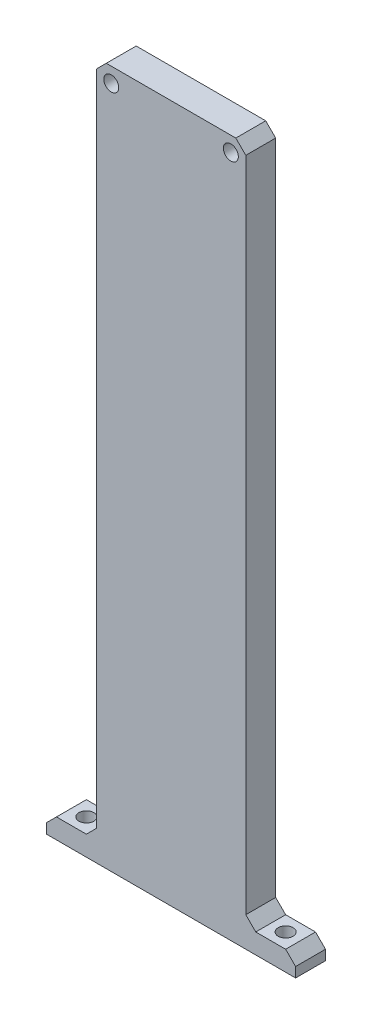
SolidWorks part; units mm, degrees
ref_plane "Front Plane" through (0, 0, 0) normal (0, 0, 1) x (1, 0, 0)
ref_plane "Top Plane" through (0, 0, 0) normal (0, 1, 0) x (1, 0, 0)
ref_plane "Right Plane" through (0, 0, 0) normal (1, 0, 0) x (0, 0, -1)
sketch "Sketch1" plane through (0, 0, 0) normal (0, 0, 1) x (1, 0, 0)
  line L1 (0, 0) -> (30, 0)
  line L2 (0, 0) -> (0, 140)
  line L3 (0, 140) -> (30, 140)
  line L4 (30, 0) -> (30, 140)
  dimension "D1" = 30
  dimension "D2" = 140
extrude "Boss-Extrude1" add sketch "Sketch1" along normal blind 6
chamfer "Chamfer1" distance 2 angle 45 2 edges at (0, 140, 3) (30, 140, 3)
sketch "Sketch2" plane through (0, 0, 6) normal (0, 0, 1) x (1, 0, 0)
  line L0 (0, 137) -> (30, 137) construction
  line L1 (0, 138) -> (0, 0) construction
  line L2 (30, 0) -> (30, 138) construction
  line L3 (28, 140) -> (2, 140) construction
  circle A0 centre (3, 137) radius 1.5
  circle A1 centre (27, 137) radius 1.5
  dimension "D2" = 3
  dimension "D3" = 3
  dimension "D1" = 3
  dimension "D4" = 3
  dimension "D5" = 3
extrude "Cut-Extrude1" cut sketch "Sketch2" against normal blind 6
sketch "Sketch3" plane through (0, 0, 0) normal (0, 1, 0) x (1, 0, 0)
  line L1 (0, 0) -> (-10, 0)
  line L2 (0, 0) -> (0, -6)
  line L3 (0, -6) -> (-10, -6)
  line L4 (-10, 0) -> (-10, -6)
  line L5 (30, 0) -> (40, 0)
  line L6 (30, 0) -> (30, -6)
  line L7 (30, -6) -> (40, -6)
  line L8 (40, 0) -> (40, -6)
  dimension "D1" = 6
  dimension "D2" = 6
  dimension "D3" = 10
  dimension "D4" = 10
extrude "Boss-Extrude2" add sketch "Sketch3" along normal blind 4
chamfer "Chamfer2" distance 2 angle 45 4 edges at (40, 4, 3) (30, 4, 3) (0, 4, 3) (-10, 4, 3)
sketch "Sketch4" plane through (0, 4, 0) normal (0, 1, 0) x (1, 0, 0)
  line L0 (-8, -3) -> (38, -3) construction
  line L1 (-8, 0) -> (-8, -6) construction
  line L2 (38, -6) -> (38, 0) construction
  line L3 (32, -6) -> (38, -6) construction
  circle A0 centre (-5, -3) radius 1.5
  circle A1 centre (35, -3) radius 1.5
  dimension "D1" = 3
  dimension "D2" = 3
  dimension "D3" = 3
extrude "Cut-Extrude2" cut sketch "Sketch4" against normal through all
